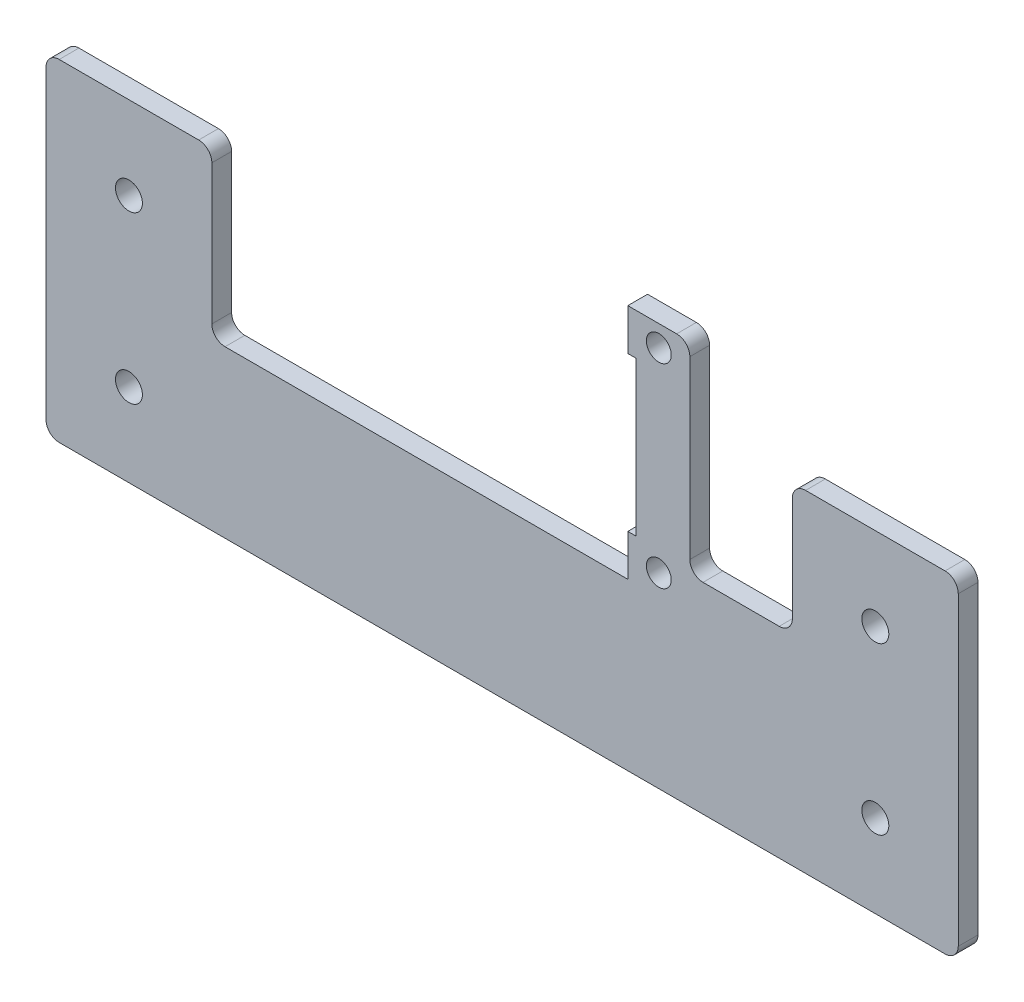
SolidWorks part; units mm, degrees
ref_plane "Front Plane" through (0, 0, 0) normal (0, 0, 1) x (1, 0, 0)
ref_plane "Top Plane" through (0, 0, 0) normal (0, 1, 0) x (1, 0, 0)
ref_plane "Right Plane" through (0, 0, 0) normal (1, 0, 0) x (0, 0, -1)
sketch "Sketch1" plane through (0, 0, 0) normal (0, 0, 1) x (1, 0, 0)
  line L0 (27.4661, -161.9069) -> (27.4661, -151.9069)
  line L1 (-112.8427, -249.0574) -> (107.1573, -249.0574)
  line L2 (-112.8427, -249.0574) -> (-112.8427, -169.0574)
  line L3 (67.1573, -169.0574) -> (107.1573, -169.0574)
  line L4 (107.1573, -169.0574) -> (107.1573, -249.0574)
  line L5 (27.4661, -151.9069) -> (42.4282, -151.9069)
  line L6 (29.5004, -161.9069) -> (27.4661, -161.9069)
  line L7 (29.5004, -161.9069) -> (29.5004, -199.0574)
  line L8 (-112.8427, -169.0574) -> (-72.8427, -169.0574)
  line L9 (-72.8427, -169.0574) -> (-72.8427, -209.0574)
  line L10 (29.5004, -199.0574) -> (27.4661, -199.0574)
  line L11 (-72.8427, -209.0574) -> (27.4661, -209.0574)
  line L12 (27.4661, -156.9869) -> (27.4661, -203.9769) construction
  line L13 (67.1573, -200.6287) -> (67.1573, -169.0574)
  line L14 (67.1573, -200.6287) -> (42.4282, -200.6287)
  line L15 (42.4282, -200.6287) -> (42.4282, -151.9069)
  line L16 (27.4661, -199.0574) -> (27.4661, -209.0574)
  circle A0 centre (-92.8427, -189.0574) radius 3.25
  circle A1 centre (87.1573, -189.0574) radius 3.25
  circle A2 centre (87.1573, -229.0574) radius 3.25
  circle A3 centre (-92.8427, -229.0574) radius 3.25
  circle A4 centre (34.9461, -203.9769) radius 3
  circle A5 centre (34.9461, -156.9869) radius 3
  dimension "D5" = 20
  dimension "D6" = 6.5
  dimension "D15" = 6.5
  dimension "D16" = 6.5
  dimension "D17" = 6.5
  dimension "D1" = 80
  dimension "D2" = 40
  dimension "D3" = 40
  dimension "D4" = 40
  dimension "D7" = 7.48
  dimension "D8" = 20
  dimension "D9" = 20
  dimension "D10" = 20
  dimension "D11" = 20
  dimension "D12" = 20
  dimension "D13" = 20
  dimension "D14" = 20
  dimension "D18" = 40
  dimension "D19" = 10
  dimension "D20" = 10
  dimension "D21" = 7.48
extrude "Boss-Extrude1" add sketch "Sketch1" along normal blind 4.7625
fillet "Fillet3" radius 3.18 10 edges at (42.4282, -200.6287, 2.3813) (67.1573, -200.6287, 2.3813) (67.1573, -169.0574, 2.3813) (107.1573, -169.0574, 2.3813) (107.1573, -249.0574, 2.3813) (-112.8427, -249.0574, 2.3813) (-72.8427, -209.0574, 2.3813) (-112.8427, -169.0574, 2.3813) (-72.8427, -169.0574, 2.3813) (42.4282, -151.9069, 2.3813)
